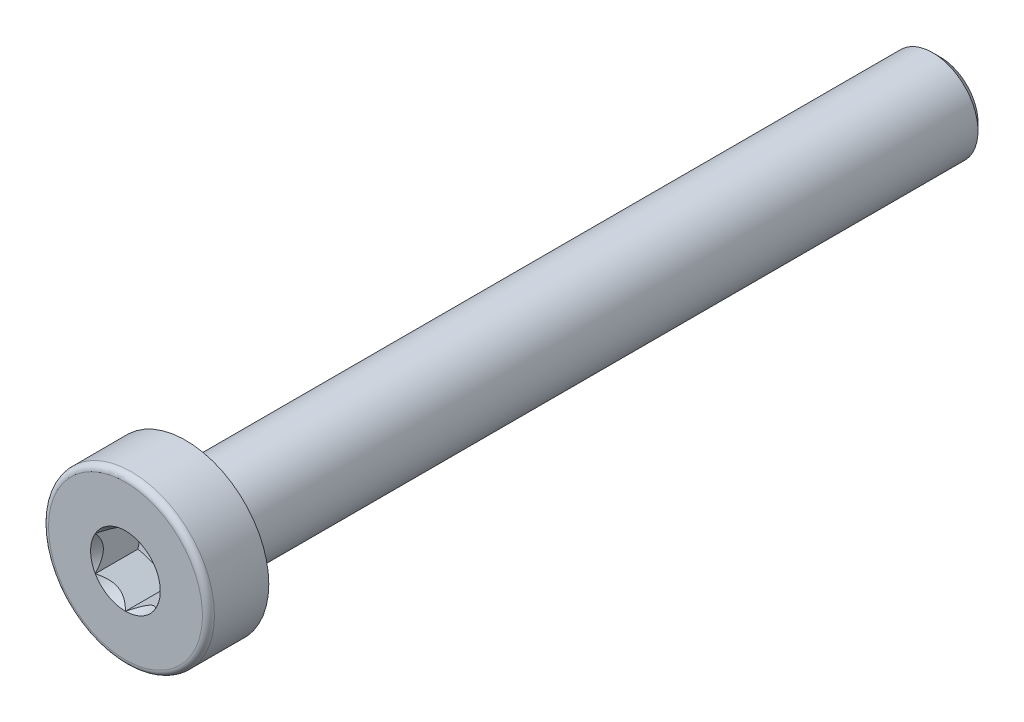
SolidWorks part; units mm, degrees
ref_plane "Front" through (0, 0, 0) normal (0, 0, 1) x (1, 0, 0)
ref_plane "Top" through (0, 0, 0) normal (0, 1, 0) x (1, 0, 0)
ref_plane "Right" through (0, 0, 0) normal (1, 0, 0) x (0, 0, -1)
sketch "Sketch1" plane through (0, 0, 0) normal (1, 0, 0) x (0, 0, -1)
  line L0 (0, 1.5) -> (0, 2.75)
  line L1 (0, 2.75) -> (-2, 2.75)
  line L2 (-2, 2.75) -> (-2, 0)
  line L3 (-2, 0) -> (25, 0)
  line L4 (25, 0) -> (25, 1.5)
  line L5 (25, 1.5) -> (0, 1.5)
  line L6 (-13.7824, 0) -> (39.7869, 0) construction
  dimension "l" = 25
  dimension "d" = 3
  dimension "k" = 2
  dimension "dk" = 5.5
revolve "Revolve1" add sketch "Sketch1" angle 360 about L6
sketch "Sketch2" plane through (0, 0, 0) normal (1, 0, 0) x (0, 0, -1)
  line L0 (0.0774, 0) -> (-0.5, 1)
  line L1 (-0.5, 1) -> (-2, 1)
  line L2 (-2, 2.75) -> (-2, -2.75) construction
  line L3 (-2, 1) -> (-2, 0)
  line L4 (-2, 0) -> (0.0774, 0)
  line L5 (0, 0) -> (-2, 0) construction
  dimension "D1" = 60
  dimension "t" = 1.5
  dimension "S" = 2
revolve "Cut-Revolve1" cut sketch "Sketch2" angle 360 about L5
sketch "Sketch3" plane through (0, 0, 2) normal (0, 0, 1) x (1, 0, 0)
  line L1 (0, 1.1547) -> (-1, 0.5774)
  line L2 (-1, 0.5774) -> (-1, -0.5774)
  line L3 (-1, -0.5774) -> (0, -1.1547)
  line L4 (0, -1.1547) -> (1, -0.5774)
  line L5 (1, -0.5774) -> (1, 0.5774)
  line L6 (1, 0.5774) -> (0, 1.1547)
  circle A0 centre (0, 0) radius 1 construction
  circle A1 centre (0, 0) radius 1 construction
extrude "Cut-Extrude1" cut sketch "Sketch3" against normal up to surface (1.4107 mm away)
sketch "Sketch4" plane through (0, 0, 0) normal (1, 0, 0) x (0, 0, -1)
  line L0 (-1.5, 0.866) -> (-2.5, 0.866)
  line L1 (-2, 2.75) -> (-2, -2.75) construction
  line L2 (-2.5, 0.866) -> (-2.5, 1.4434)
  line L3 (-2.5, 1.4434) -> (-1.5, 0.866)
  line L4 (0, 0) -> (-2, 0) construction
  dimension "D1" = 30
  dimension "D2" = 1
revolve "Cut-Revolve2" cut sketch "Sketch4" angle 360 about L4
chamfer "Chamfer1" distance 0.25 angle 45 1 edges at (1.5, 0, -25)
fillet "Fillet1" radius 0.2 1 edges at (2.75, 0, 2)
equation "\"D1@Fillet1\" = \"k@Sketch1\" / 10"
equation "\"D2@Sketch4\" = \"S@Sketch2\" / 2"
